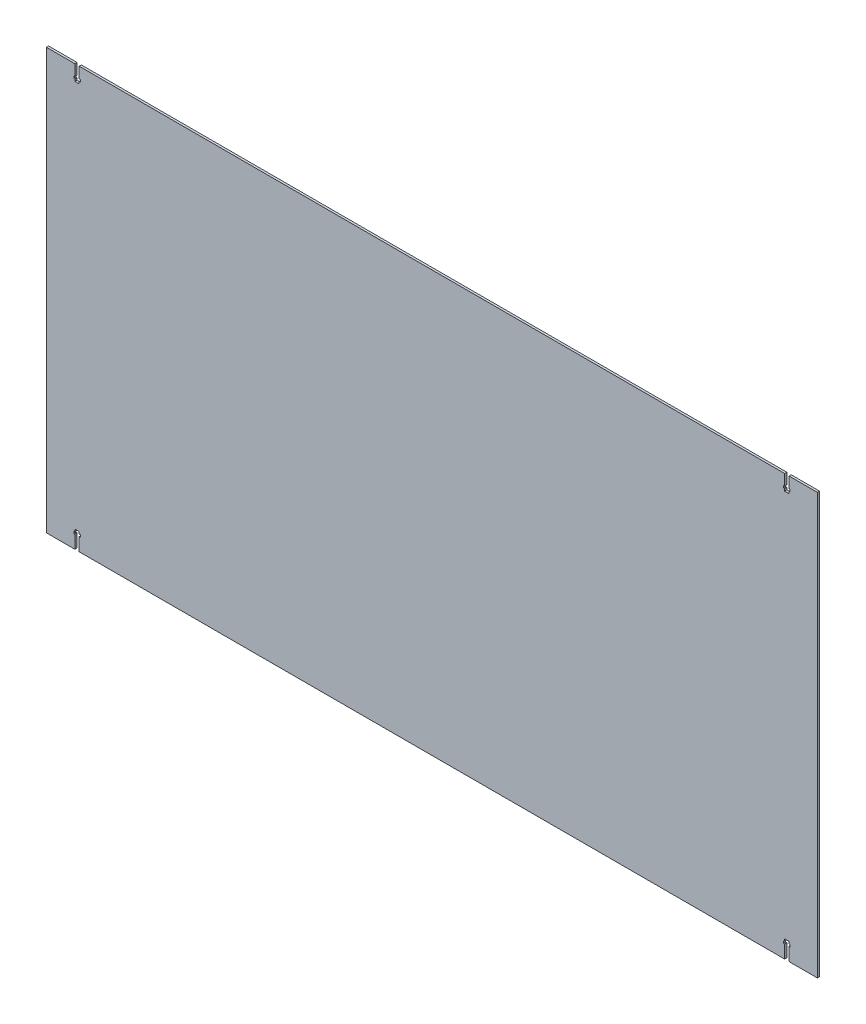
SolidWorks part; units mm, degrees
material "Acrylic (Medium-high impact)"
ref_plane "Front Plane" through (0, 0, 0) normal (0, 0, 1) x (1, 0, 0)
ref_plane "Top Plane" through (0, 0, 0) normal (0, 1, 0) x (1, 0, 0)
ref_plane "Right Plane" through (0, 0, 0) normal (1, 0, 0) x (0, 0, -1)
sketch "Sketch1" plane through (0, 0, 0) normal (0, 0, 1) x (1, 0, 0)
  line L1 (0, 0) -> (1117.6, 0)
  line L2 (0, 0) -> (0, 609.6)
  line L3 (0, 609.6) -> (1117.6, 609.6)
  line L4 (1117.6, 0) -> (1117.6, 609.6)
  dimension "D1" = 1117.6
  dimension "D2" = 609.6
extrude "Boss-Extrude1" add sketch "Sketch1" along normal blind 3.175
sketch "Sketch4" plane through (0, 612.775, 0) normal (0, 1, 0) x (1, 0, 0)
  line L1 (41.2545, -3.175) -> (47.6045, -3.175)
  line L2 (41.2545, -3.175) -> (41.2545, 0)
  line L3 (41.2545, 0) -> (47.6045, 0)
  line L4 (47.6045, -3.175) -> (47.6045, 0)
extrude "Cut-Extrude2" cut sketch "Sketch4" against normal blind 25.4
sketch "Sketch5" plane through (0, 0, 3.175) normal (0, 0, 1) x (1, 0, 0)
  line L0 (41.2545, 587.375) -> (41.2545, 609.6) construction
  line L1 (39.667, 593.725) -> (49.192, 593.725)
  line L2 (39.667, 593.725) -> (39.667, 590.55)
  line L3 (39.667, 590.55) -> (49.192, 590.55)
  line L4 (49.192, 593.725) -> (49.192, 590.55)
  line L5 (41.2545, 587.375) -> (47.6045, 587.375) construction
  point P6 (44.4295, 590.55)
  dimension "D1" = 9.525
  dimension "D2" = 3.175
  dimension "D3" = 1.5875
  dimension "D4" = 3.175
extrude "Cut-Extrude3" cut sketch "Sketch5" against normal blind 25.4
ref_plane "Plane1" through (558.8, 0, 0) normal (-1, 0, 0) x (0, 0, 1)
mirror "Mirror1" about plane through (558.8, 0, 0) normal (-1, 0, 0) of "Cut-Extrude2", "Cut-Extrude3"
ref_plane "Plane2" through (0, 306.3875, 0) normal (0, 1, 0) x (1, 0, 0)
mirror "Mirror2" about plane through (0, 306.3875, 0) normal (0, 1, 0) of "Mirror1", "Cut-Extrude2", "Cut-Extrude3"
equation "\"W\"= 44in'width"
equation "\"L\"= 24in'length"
equation "\"t\"= 1 / 8in'thickness"
equation "\"D1@Sketch1\"=\"W\""
equation "\"D2@Sketch1\"=\"L\""
equation "\"D1@Boss-Extrude1\"=\"t\""
